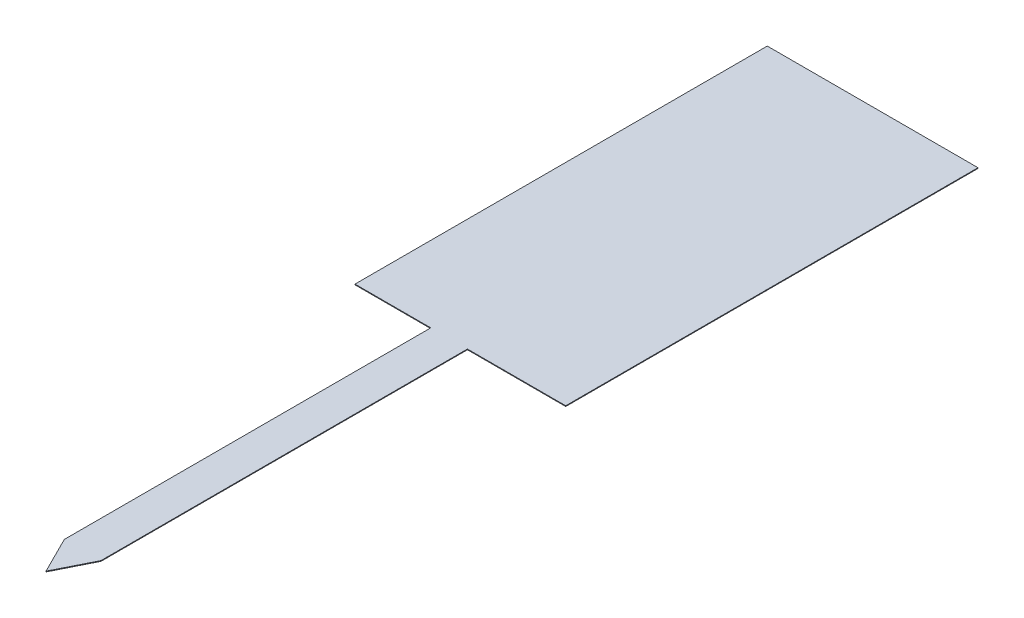
SolidWorks part; units mm, degrees
ref_plane "Front Plane" through (0, 0, 0) normal (0, 0, 1) x (1, 0, 0)
ref_plane "Top Plane" through (0, 0, 0) normal (0, 1, 0) x (1, 0, 0)
ref_plane "Right Plane" through (0, 0, 0) normal (1, 0, 0) x (0, 0, -1)
sketch "Sketch5" plane through (-4.1516, 0, 2.1215) normal (0, 1, 0) x (1, 0, 0)
  line L10 (6.1516, -20.3785) -> (2.1516, -20.3785)
  line L22 (-6.1221, 24.6215) -> (16.8779, 24.6215)
  line L23 (16.8779, 24.6215) -> (16.8779, -20.3785)
  line L24 (16.8779, -20.3785) -> (6.1516, -20.3785)
  line L25 (6.1516, -20.3785) -> (6.1516, -60.3785)
  line L26 (6.1516, -60.3785) -> (4.1516, -64.3785)
  line L27 (4.1516, -64.3785) -> (2.1516, -60.3785)
  line L28 (2.1516, -60.3785) -> (2.1516, -20.3785)
  line L29 (2.1516, -20.3785) -> (-6.1221, -20.3785)
  line L30 (-6.1221, -20.3785) -> (-6.1221, 24.6215)
  point P0 (-6.1221, 2.1215)
  point P1 (-8.3484, 24.6215)
  point P2 (0, 0)
  point P3 (0, 0)
  point P4 (2.1516, -20.3785)
  point P5 (0, 0)
  point P6 (0, 0)
  point P19 (4.1516, 24.6215)
  dimension "D2" = 8.2736
  dimension "D6" = 4
  dimension "D7" = 45
  dimension "D8" = 23
  dimension "D9" = 40
  dimension "D10" = 4
extrude "Boss-Extrude3" add sketch "Sketch5" along normal blind 0.075 contours L29 L30 L22 L23 L24 L25 L26 L27 L28
sketch "Circuit" plane through (0, 0.075, 0) normal (0, 1, 0) x (1, 0, 0)
  line L0 (1.6998, -0.2689) -> (1.6998, -2.65)
  line L1 (1.6998, -2.65) -> (-1.1772, -5.527)
  line L2 (-1.1772, -5.527) -> (-1.0879, -14.4459)
  line L3 (-1.0879, -14.4459) -> (-0.6068, -14.9271)
  line L4 (-0.6068, -14.9271) -> (-0.6068, -17.953)
  line L5 (-0.6068, -17.953) -> (-1.1772, -18.5234)
  line L6 (-1.1772, -18.5234) -> (-1.1772, -19.4957)
  line L7 (-1.1772, -19.4957) -> (-1.1772, -21.212)
  line L8 (-1.1772, -21.212) -> (-1.1475, -62.3341)
  line L9 (-0.954, -12.9677) -> (-1.1027, -12.9677)
  line L10 (3.5848, -0.765) -> (3.5848, -4.6341)
  line L11 (3.5848, -4.6341) -> (1.303, -6.916)
  line L12 (1.303, -6.916) -> (0.7078, -6.916)
  line L13 (1.303, -6.916) -> (1.303, -10.7851)
  line L14 (1.303, -10.7851) -> (1.7991, -11.2812)
  line L15 (1.7991, -11.2812) -> (1.7991, -12.9677)
  line L16 (1.7991, -12.9677) -> (1.9975, -13.1661)
  line L17 (1.9975, -13.1661) -> (1.9975, -18.0274)
  line L18 (1.9975, -18.0274) -> (0.6085, -18.0274)
  line L19 (0.6085, -18.0274) -> (0.0381, -17.4569)
  line L20 (0.0381, -17.4569) -> (0.0381, -14.9767)
  line L21 (0.0381, -14.9767) -> (-0.0115, -14.9271)
  line L22 (-0.0115, -14.9271) -> (-0.6068, -14.9271)
  line L23 (1.9975, -18.0274) -> (1.9975, -21.4997)
  line L24 (1.9975, -21.4997) -> (0.807, -22.6902)
  line L25 (0.807, -22.6902) -> (0.807, -62.1555)
  line L26 (0.7078, -6.7919) -> (0.7078, -7.04)
  line L27 (0.7078, -6.7919) -> (-0.582, -6.7919)
  line L28 (-0.582, -6.7919) -> (-0.582, -7.04)
  line L29 (0.7078, -7.04) -> (-0.582, -7.04)
  line L30 (1.5923, -8.9146) -> (1.5923, -9.9067)
  line L31 (1.5923, -8.9146) -> (0.9971, -8.9146)
  line L32 (0.9971, -8.9146) -> (0.9971, -9.9067)
  line L33 (1.5923, -9.9067) -> (0.9971, -9.9067)
  line L34 (2.4654, -19.0597) -> (2.4654, -20.5479)
  line L35 (2.4654, -19.0597) -> (1.4733, -19.0597)
  line L36 (1.4733, -19.0597) -> (1.4733, -20.5479)
  line L37 (2.4654, -20.5479) -> (1.4733, -20.5479)
  line L38 (1.4112, -61.7682) -> (1.4112, -62.5619)
  line L39 (1.4112, -61.7682) -> (-1.5651, -61.7682)
  line L40 (-1.5651, -61.7682) -> (-1.5651, -62.5619)
  line L41 (1.4112, -62.5619) -> (-1.5651, -62.5619)
  line L42 (0.6333, -12.5885) -> (0.6333, -13.3822)
  line L43 (0.6333, -12.5885) -> (-0.954, -12.5885)
  line L44 (-0.954, -12.5885) -> (-0.954, -13.3822)
  line L45 (0.6333, -13.3822) -> (-0.954, -13.3822)
  line L46 (0.1917, -15.879) -> (0.1917, -16.8711)
  line L47 (0.1917, -15.879) -> (-0.8004, -15.879)
  line L48 (-0.8004, -15.879) -> (-0.8004, -16.8711)
  line L49 (0.1917, -16.8711) -> (-0.8004, -16.8711)
  line L50 (-0.582, -6.916) -> (-1.1633, -6.916)
sketch "Antenna" plane through (0, 0.075, 0) normal (0, 1, 0) x (1, 0, 0)
  spline S2 degree 3 poles (1.6998, 4.7311) (2.7061, 4.705) (3.7247, 4.9309) (5.5468, 5.8458) (6.3484, 6.534) (7.5382, 8.221) (7.9252, 9.2182) (8.1818, 11.2923) (8.051, 12.3672) (7.2898, 14.341) (6.6599, 15.238) (5.0384, 16.6361) (4.0482, 17.1358) (2.4625, 17.491) (1.9178, 17.5446) (0.8285, 17.5171) (0.2839, 17.4361) (-0.7722, 17.143) (-1.2837, 16.9308) (-2.2425, 16.3865) (-2.6897, 16.0544) (-3.4919, 15.289) (-3.847, 14.8556) (-4.4425, 13.9127) (-4.683, 13.4032) (-5.0334, 12.3377) (-5.1434, 11.7818) (-5.2247, 10.6567) (-5.1961, 10.0875) (-5.0004, 8.9701) (-4.8333, 8.4219) (-4.3692, 7.3798) (-4.0722, 6.8859) (-3.3647, 5.9828) (-2.9543, 5.5737) (-2.0435, 4.8657) (-1.5431, 4.567) (-0.4817, 4.0991) (0.0793, 3.9301) (1.229, 3.7332) (1.8175, 3.7054) (2.9869, 3.7944) (3.5677, 3.9112) (4.6864, 4.2838) (5.2243, 4.5397) (6.2242, 5.1765) (6.6863, 5.5575) (7.5058, 6.4229) (7.8633, 6.9074) (8.451, 7.9517) (8.6812, 8.5115) (8.9991, 9.6735) (9.0868, 10.2756) (9.1129, 11.4865) (9.0512, 12.0951) (8.7807, 13.2821) (8.5719, 13.8605) (8.018, 14.9519) (7.6731, 15.4649) (6.8664, 16.3937) (6.4046, 16.8096) (5.3911, 17.5181) (4.8393, 17.8108) (3.6779, 18.254) (3.0684, 18.4045) (1.8278, 18.5528) (1.1968, 18.5507) (-0.049, 18.3922) (-0.6637, 18.2359) (-1.8395, 17.777) (-2.4006, 17.4745) (-3.4349, 16.7398) (-3.908, 16.3078) (-4.7368, 15.3389) (-5.0925, 14.8022) (-5.6638, 13.6552) (-5.8793, 13.045) (-6.1561, 11.7873) (-6.2172, 11.1398) (-6.1797, 9.8462) (-6.0811, 9.2001) (-5.7286, 7.9483) (-5.4746, 7.3425) (-4.8252, 6.2084) (-4.4297, 5.68) (-3.5196, 4.7331) (-3.0051, 4.3146) (-1.8867, 3.6139) (-1.283, 3.3317) (-0.0218, 2.9219) (0.6356, 2.7944) (1.965, 2.703) (2.6369, 2.7392) (3.9549, 2.9748) (4.601, 3.1742) (5.828, 3.7257) (6.4089, 4.0779) (7.4701, 4.9151) (7.9503, 5.4001) (8.7801, 6.4752) (9.1296, 7.0652) (9.6758, 8.3156) (9.8723, 8.976) (10.0992, 10.3279) (10.1295, 11.0195) (10.0204, 12.3924) (9.8811, 13.0737) (9.4395, 14.385) (9.1374, 15.0149) (8.3869, 16.1849) (7.9386, 16.725) (6.9216, 17.6819) (6.3529, 18.0987) (5.1283, 18.7828) (4.4723, 19.0501) (3.1119, 19.4177) (2.4075, 19.518) (0.9922, 19.5441) (0.2813, 19.4698) (-1.1042, 19.1496) (-1.7787, 18.9037) (-3.0505, 18.2534) (-3.6476, 17.8491) (-4.728, 16.9051) (-5.2112, 16.3653) (-6.0334, 15.1817) (-6.3724, 14.5379) (-6.8845, 13.184) (-7.0575, 12.4739) (-7.226, 11.0298) (-7.2212, 10.2958) (-7.0328, 8.8477) (-6.849, 8.1337) (-6.3119, 6.7688) (-5.9585, 6.1181) (-5.102, 4.9196) (-4.599, 4.3718) (-3.472, 3.4133) (-2.8482, 3.0025) (-1.5163, 2.3437) (-0.8083, 2.0958) (0.65, 1.7792) (1.4002, 1.7105) (2.8982, 1.758) (3.6458, 1.8742) (5.0934, 2.2861) (5.7933, 2.5818) (7.1029, 3.3364) (7.7125, 3.7953) (8.804, 4.85) (9.2859, 5.4458) (10.0917, 6.7396) (10.4156, 7.4375) (10.8848, 8.8945) (11.03, 9.6534) (11.1314, 11.187) (11.0876, 11.9617) (10.8121, 13.4803) (10.5804, 14.2242) (9.9414, 15.6361) (9.5342, 16.3041) (8.5672, 17.5234) (8.0075, 18.0746) (6.7681, 19.0262) (6.0885, 19.4265) (4.6491, 20.0509) (3.8895, 20.275) (2.3352, 20.5319) (1.5407, 20.5647) (-0.0358, 20.4356) (-0.8176, 20.2737) (-2.3215, 19.7632) (-3.0434, 19.4147) (-4.3835, 18.5506) (-5.0016, 18.0351) (-6.0959, 16.8665) (-6.572, 16.2136) (-7.3525, 14.8085) (-7.6569, 14.0565) (-8.0742, 12.4977) (-8.1871, 11.691) (-8.2132, 10.0711) (-8.1263, 9.258) (-7.7564, 7.6741) (-7.4734, 6.9035) (-6.7267, 5.4513) (-6.2631, 4.7699) (-5.1817, 3.5379) (-4.5639, 2.9875) (-3.2103, 2.0517) (-2.4744, 1.6664) (-0.9279, 1.0854) (-0.1173, 0.8897) (1.5304, 0.7012) (2.3674, 0.7085) (4.0178, 0.927) (4.8311, 1.1382) (6.3849, 1.7536) (7.1253, 2.1578) (8.4881, 3.1361) (9.1104, 3.7102) (10.1988, 4.9953) (10.6647, 5.7062) (11.4109, 7.2229) (11.6911, 8.0288) (12.0476, 9.6877) (12.1239, 10.5406) (12.0663, 12.2428) (11.9325, 13.092) (11.4612, 14.7353) (11.1238, 15.5294) (10.2641, 17.0144) (9.7418, 17.7053) (8.5425, 18.9414) (7.8655, 19.4867) (6.3962, 20.3976) (5.6041, 20.7633) (3.9514, 21.2919) (3.091, 21.4547) (1.3531, 21.5661) (0.4756, 21.5148) (-1.2436, 21.1994) (-2.0853, 20.9353) (-3.6821, 20.2089) (-4.4371, 19.7465) (-5.8145, 18.6498) (-6.4368, 18.0155) (-7.5103, 16.6118) (-7.9614, 15.8425) (-8.664, 14.2142) (-8.9155, 13.3553) (-9.2024, 11.5987) (-9.2378, 10.7011) (-9.0886, 8.9211) (-8.9041, 8.0388) (-8.3248, 6.3423) (-7.93, 5.5283) (-6.9523, 4.0182) (-6.3694, 3.3221) (-5.0493, 2.0905) (-4.3121, 1.555) (-2.7267, 0.678) (-1.8785, 0.3366) (-0.1213, -0.1304) (0.7876, -0.2559) (1.6998, -0.2689) knots 0 0 0 0 0.015625 0.015625 0.03125 0.03125 0.046875 0.046875 0.0625 0.0625 0.078125 0.078125 0.09375 0.09375 0.101562 0.101562 0.109375 0.109375 0.117188 0.117188 0.125 0.125 0.132812 0.132812 0.140625 0.140625 0.148438 0.148438 0.15625 0.15625 0.164062 0.164062 0.171875 0.171875 0.179688 0.179688 0.1875 0.1875 0.195312 0.195312 0.203125 0.203125 0.210938 0.210938 0.21875 0.21875 0.226562 0.226562 0.234375 0.234375 0.242188 0.242188 0.25 0.25 0.257812 0.257812 0.265625 0.265625 0.273438 0.273438 0.28125 0.28125 0.289062 0.289062 0.296875 0.296875 0.304688 0.304688 0.3125 0.3125 0.320312 0.320312 0.328125 0.328125 0.335938 0.335938 0.34375 0.34375 0.351562 0.351562 0.359375 0.359375 0.367188 0.367188 0.375 0.375 0.382812 0.382812 0.390625 0.390625 0.398438 0.398438 0.40625 0.40625 0.414062 0.414062 0.421875 0.421875 0.429688 0.429688 0.4375 0.4375 0.445312 0.445312 0.453125 0.453125 0.460938 0.460938 0.46875 0.46875 0.476562 0.476562 0.484375 0.484375 0.492188 0.492188 0.5 0.5 0.507812 0.507812 0.515625 0.515625 0.523438 0.523438 0.53125 0.53125 0.539062 0.539062 0.546875 0.546875 0.554688 0.554688 0.5625 0.5625 0.570312 0.570312 0.578125 0.578125 0.585938 0.585938 0.59375 0.59375 0.601562 0.601562 0.609375 0.609375 0.617188 0.617188 0.625 0.625 0.632812 0.632812 0.640625 0.640625 0.648438 0.648438 0.65625 0.65625 0.664062 0.664062 0.671875 0.671875 0.679688 0.679688 0.6875 0.6875 0.695312 0.695312 0.703125 0.703125 0.710938 0.710938 0.71875 0.71875 0.726562 0.726562 0.734375 0.734375 0.742188 0.742188 0.75 0.75 0.757812 0.757812 0.765625 0.765625 0.773438 0.773438 0.78125 0.78125 0.789062 0.789062 0.796875 0.796875 0.804688 0.804688 0.8125 0.8125 0.820312 0.820312 0.828125 0.828125 0.835938 0.835938 0.84375 0.84375 0.851562 0.851562 0.859375 0.859375 0.867188 0.867188 0.875 0.875 0.882812 0.882812 0.890625 0.890625 0.898438 0.898438 0.90625 0.90625 0.914062 0.914062 0.921875 0.921875 0.929688 0.929688 0.9375 0.9375 0.945312 0.945312 0.953125 0.953125 0.960938 0.960938 0.96875 0.96875 0.976562 0.976562 0.984375 0.984375 0.992188 0.992188 1 1 1 1
  point P1 (0, 0)
